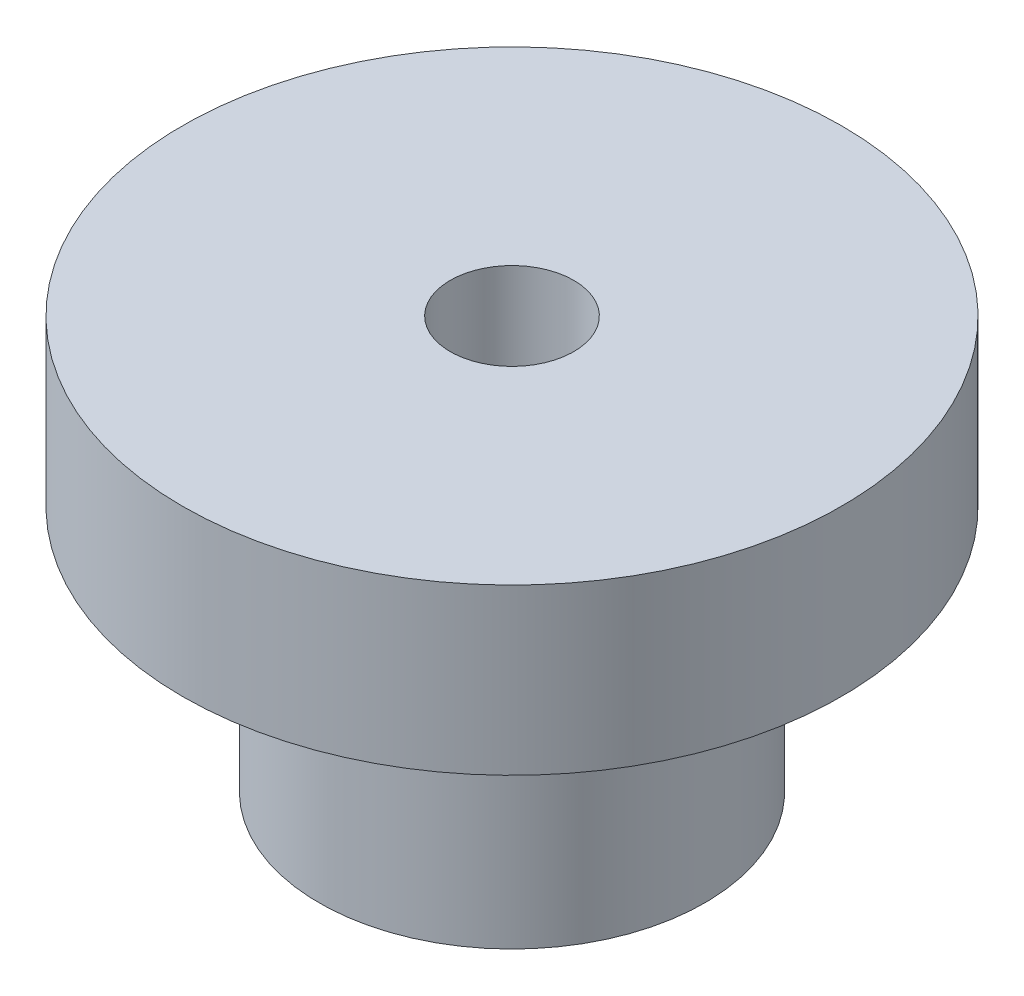
SolidWorks part; units mm, degrees
ref_plane "Front Plane" through (0, 0, 0) normal (0, 0, 1) x (1, 0, 0)
ref_plane "Top Plane" through (0, 0, 0) normal (0, 1, 0) x (1, 0, 0)
ref_plane "Right Plane" through (0, 0, 0) normal (1, 0, 0) x (0, 0, -1)
sketch "Sketch1" plane through (0, 0, 0) normal (0, 1, 0) x (1, 0, 0)
  circle A0 centre (-27.1992, 0) radius 3.7147
  circle A1 centre (-27.1992, 0) radius 1.1906
extrude "Boss-Extrude1" add sketch "Sketch1" along normal blind 4.7625
sketch "Sketch3" plane through (0, 4.7625, 0) normal (0, 1, 0) x (1, 0, 0)
  circle A0 centre (-27.1992, 0) radius 6.35
  circle A1 centre (-27.1992, 0) radius 1.1906
extrude "Boss-Extrude2" add sketch "Sketch3" along normal blind 3.175
